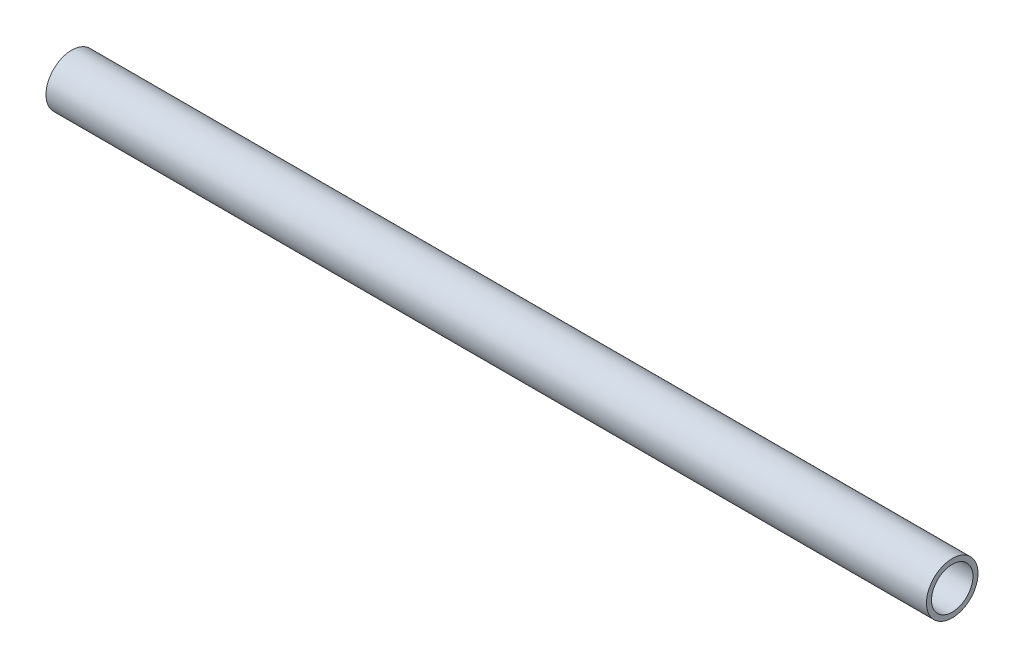
SolidWorks part; units mm, degrees
ref_plane "Vorne" through (0, 0, 0) normal (0, 0, 1) x (1, 0, 0)
ref_plane "Oben" through (0, 0, 0) normal (0, 1, 0) x (1, 0, 0)
ref_plane "Seite" through (0, 0, 0) normal (1, 0, 0) x (0, 0, -1)
sketch "Skizze1" plane through (0, 0, 0) normal (1, 0, 0) x (0, 0, -1)
  circle A0 centre (0, 0) radius 2.05
  circle A1 centre (0, 0) radius 2.55
  dimension "D1" = 4.1
  dimension "D2" = 5.1
extrude "Aufsatz-Linear austragen1" add sketch "Skizze1" along normal blind 87.15
